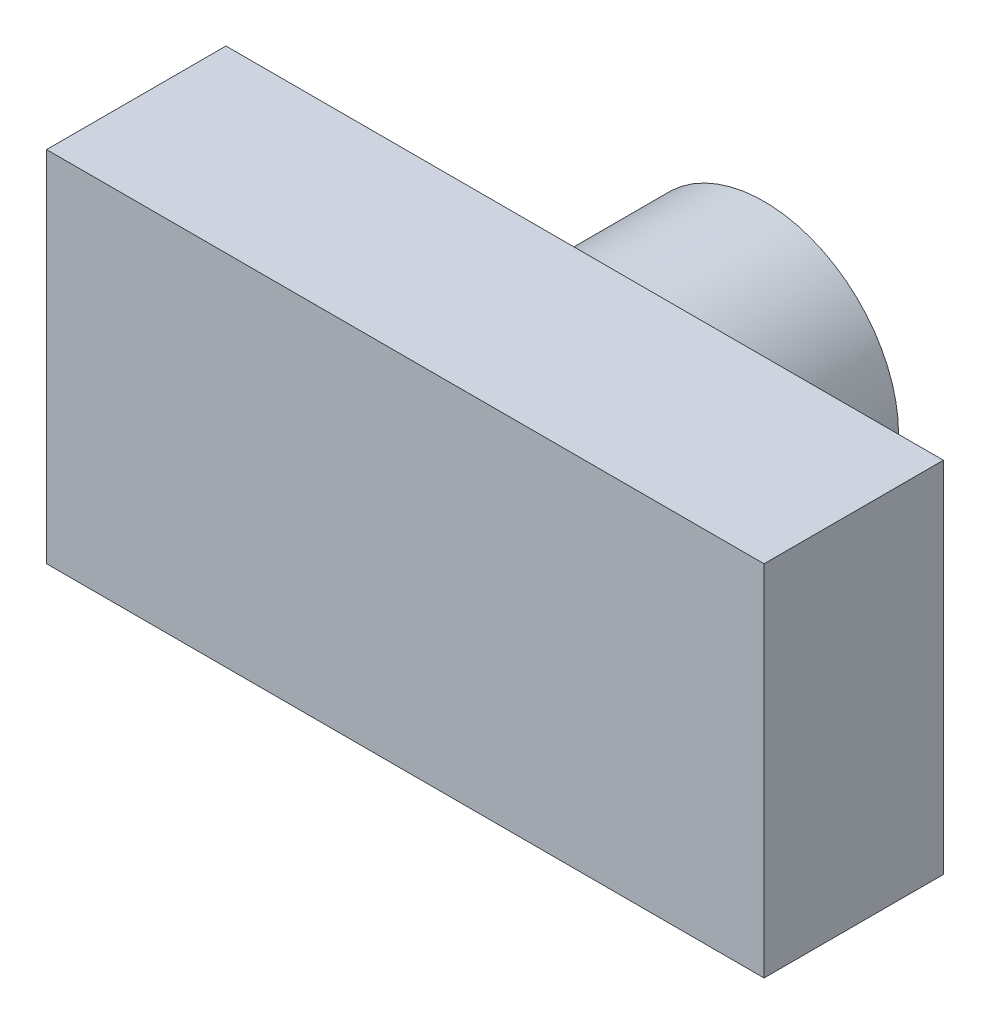
SolidWorks part; units mm, degrees
ref_plane "Front Plane" through (0, 0, 0) normal (0, 0, 1) x (1, 0, 0)
ref_plane "Top Plane" through (0, 0, 0) normal (0, 1, 0) x (1, 0, 0)
ref_plane "Right Plane" through (0, 0, 0) normal (1, 0, 0) x (0, 0, -1)
sketch "Sketch1" plane through (0, 0, 0) normal (0, 0, 1) x (1, 0, 0)
  line L1 (-50.8, -25.4) -> (50.8, -25.4)
  line L2 (-50.8, -25.4) -> (-50.8, 25.4)
  line L3 (-50.8, 25.4) -> (50.8, 25.4)
  line L4 (50.8, -25.4) -> (50.8, 25.4)
  line L5 (-50.8, -25.4) -> (50.8, 25.4) construction
  line L6 (-50.8, 25.4) -> (50.8, -25.4) construction
  point P0 (0, 0)
  dimension "D1" = 101.6
  dimension "D2" = 50.8
extrude "Boss-Extrude1" add sketch "Sketch1" along normal blind 25.4
sketch "Sketch2" plane through (0, 0, 0) normal (0, 0, -1) x (-1, 0, 0)
  circle A0 centre (0, 0) radius 19.05
  dimension "D1" = 38.1
extrude "Boss-Extrude2" add sketch "Sketch2" along normal blind 25.4
